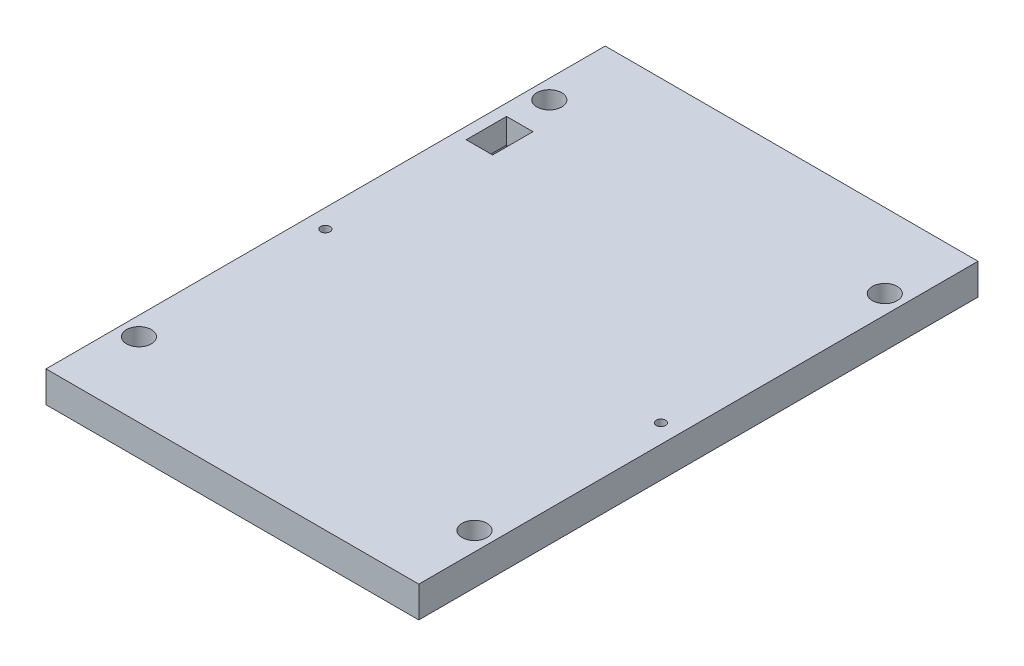
SolidWorks part; units mm, degrees
material "Acrylic (Medium-high impact)"
ref_plane "Front Plane" through (0, 0, 0) normal (0, 0, 1) x (1, 0, 0)
ref_plane "Top Plane" through (0, 0, 0) normal (0, 1, 0) x (1, 0, 0)
ref_plane "Right Plane" through (0, 0, 0) normal (1, 0, 0) x (0, 0, -1)
sketch "Sketch1" plane through (0, 0, 0) normal (0, 1, 0) x (1, 0, 0)
  line L0 (-19.5725, 105.4275) -> (-19.5725, -74.5725) construction
  line L1 (40.4275, -74.5725) -> (-79.5725, -74.5725)
  line L2 (40.4275, -74.5725) -> (40.4275, 105.4275)
  line L3 (40.4275, 105.4275) -> (-79.5725, 105.4275)
  line L4 (-79.5725, -74.5725) -> (-79.5725, 105.4275)
  line L6 (40.4275, 15.4275) -> (-79.5725, 15.4275) construction
  point P0 (0, 0)
  dimension "D1" = 120
  dimension "D2" = 180
extrude "Boss-Extrude1" add sketch "Sketch1" along normal blind 10
sketch "Sketch2" plane through (0, 0, 0) normal (0, -1, 0) x (1, 0, 0)
  circle A8 centre (-73.5725, 50.6502) radius 4
  circle A9 centre (34.4275, 50.6502) radius 4
  circle A10 centre (34.4275, -81.4275) radius 4
  circle A11 centre (-73.5725, -81.4275) radius 4
  circle A12 centre (-73.5725, -9.3498) radius 1.5
  circle A13 centre (34.4275, -9.3498) radius 1.5
  point P10 (0, 0)
  dimension "D1" = 3
  dimension "D2" = 3
  dimension "D3" = 60
  dimension "D4" = 60
extrude "Cut-Extrude1" cut sketch "Sketch2" against normal blind 10
sketch "Sketch3" plane through (0, 0, 0) normal (0, -1, 0) x (1, 0, 0)
  line L5 (13.3217, 18.0764) -> (-53.6783, 18.0764)
  line L6 (13.3217, 18.0764) -> (13.3217, 72.0764)
  line L7 (13.3217, 72.0764) -> (-53.6783, 72.0764)
  line L8 (-53.6783, 18.0764) -> (-53.6783, 72.0764)
  line L9 (13.3217, 18.0764) -> (-53.6783, 72.0764) construction
  line L10 (13.3217, 72.0764) -> (-53.6783, 18.0764) construction
  line L16 (27.8739, -96.8285) -> (-57.1261, -96.8285)
  line L21 (-76.7495, -56.0775) -> (-66.3895, -56.0775)
  line L22 (-76.7495, -56.0775) -> (-76.7495, -70.7775)
  line L23 (-76.7495, -70.7775) -> (-66.3895, -70.7775)
  line L24 (-66.3895, -56.0775) -> (-66.3895, -70.7775)
  line L25 (-76.7495, -56.0775) -> (-66.3895, -70.7775) construction
  line L26 (-76.7495, -70.7775) -> (-66.3895, -56.0775) construction
  line L27 (27.8739, -96.8285) -> (27.8739, -55.8285)
  line L28 (27.8739, -55.8285) -> (-57.1261, -55.8285)
  line L29 (-57.1261, -96.8285) -> (-57.1261, -55.8285)
  line L30 (27.8739, -96.8285) -> (-57.1261, -55.8285) construction
  line L31 (27.8739, -55.8285) -> (-57.1261, -96.8285) construction
  point P0 (-20.1783, 45.0764)
  point P5 (-14.6261, -76.3285)
  point P10 (-71.5695, -63.4275)
  point P15 (-14.474, -68.3258)
  point P16 (-15.7911, -77.1336)
  point P17 (-14.8018, -76.1528)
  point P18 (-14.6261, -76.3285)
  dimension "D1" = 67
  dimension "D2" = 54
  dimension "D3" = 85
  dimension "D4" = 41
  dimension "D5" = 10.36
  dimension "D6" = 14.7
extrude "Cut-Extrude2" cut sketch "Sketch3" against normal blind 2
sketch "Sketch4" plane through (0, 0, 0) normal (0, -1, 0) x (1, 0, 0)
  line L1 (-67.3195, -69.9275) -> (-75.8195, -69.9275)
  line L2 (-67.3195, -69.9275) -> (-67.3195, -56.9275)
  line L3 (-67.3195, -56.9275) -> (-75.8195, -56.9275)
  line L4 (-75.8195, -69.9275) -> (-75.8195, -56.9275)
  line L5 (-67.3195, -69.9275) -> (-75.8195, -56.9275) construction
  line L6 (-67.3195, -56.9275) -> (-75.8195, -69.9275) construction
  point P0 (-71.5695, -63.4275)
  point P5 (-71.5695, -63.4275)
  point P7 (-71.5695, -63.4275)
  dimension "D1" = 13
  dimension "D2" = 8.5
extrude "Cut-Extrude3" cut sketch "Sketch4" against normal blind 10
